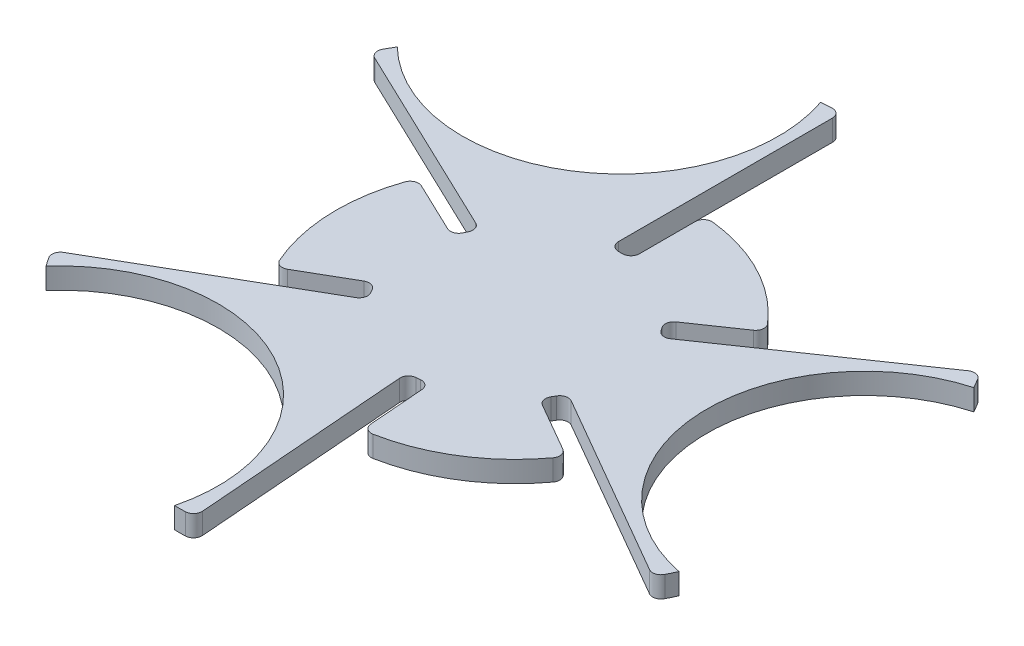
SolidWorks part; units mm, degrees
ref_plane "前基準面" through (0, 0, 0) normal (0, 0, 1) x (1, 0, 0)
ref_plane "上基準面" through (0, 0, 0) normal (0, 1, 0) x (1, 0, 0)
ref_plane "右基準面" through (0, 0, 0) normal (1, 0, 0) x (0, 0, -1)
sketch "草圖1" plane through (0, 0, 0) normal (0, 1, 0) x (1, 0, 0)
  line L2 (37.9923, -19.0481) -> (22.9006, -10.3349)
  line L8 (-2.5, 42.4264) -> (-2.5, 25)
  line L9 (-2.5, 25) -> (2.5, 25)
  line L10 (2.5, 42.4264) -> (2.5, 25)
  line L11 (22.9006, -10.3349) -> (20.4006, -14.6651)
  line L12 (35.4923, -23.3783) -> (20.4006, -14.6651)
  line L13 (-35.4923, -23.3783) -> (-20.4006, -14.6651)
  line L14 (-20.4006, -14.6651) -> (-22.9006, -10.3349)
  line L15 (-37.9923, -19.0481) -> (-22.9006, -10.3349)
  line L16 (20.6126, 14.1465) -> (0, 0) construction
  line L17 (4.4373, -24.7297) -> (5.793, -42.1033)
  line L18 (22.0272, 12.0852) -> (36.3953, 21.9461)
  line L19 (19.1979, 16.2077) -> (33.566, 26.0686)
  line L20 (19.1979, 16.2077) -> (22.0272, 12.0852)
  line L21 (-0.5475, -25.1187) -> (0.8082, -42.4923)
  line L22 (4.4373, -24.7297) -> (-0.5475, -25.1187)
  line L23 (-23.6352, 8.522) -> (-39.3591, 16.0347)
  line L24 (-21.4797, 13.0335) -> (-37.2035, 20.5462)
  line L25 (-23.6352, 8.522) -> (-21.4797, 13.0335)
  arc A35 (-2.5, 42.4264) -> (-37.2035, 20.5462) centre (0, 0) ccw
  circle A36 centre (0, 0) radius 25 construction
  arc A37 (37.9923, -19.0481) -> (36.3953, 21.9461) centre (0, 0) ccw
  arc A38 (-35.4923, -23.3783) -> (0.8082, -42.4923) centre (0, 0) ccw
  arc A39 (33.566, 26.0686) -> (2.5, 42.4264) centre (0, 0) ccw
  arc A40 (-39.3591, 16.0347) -> (-37.9923, -19.0481) centre (0, 0) ccw
  arc A41 (5.793, -42.1033) -> (35.4923, -23.3783) centre (0, 0) ccw
  point P1 (0, 25)
  dimension "D1" = 85
  dimension "D2" = 5
  dimension "D3" = 50
  dimension "D4" = 55.538
  dimension "D5" = 3
extrude "填料-伸長1" add sketch "草圖1" against normal blind 5
sketch "草圖2" plane through (0, 0, 0) normal (0, 1, 0) x (1, 0, 0)
  line L0 (-35.4923, -23.3783) -> (-67.9982, -42.1455)
  line L1 (0.8082, -42.4923) -> (3.7282, -79.9131)
  line L2 (-37.2727, -70.7866) -> (0, 0) construction
  line L3 (-0.5475, -25.1187) -> (0.8082, -42.4923) construction
  line L4 (-35.4923, -23.3783) -> (-20.4006, -14.6651) construction
  line L5 (-2.5, 42.4264) -> (-2.5, 79.9609)
  line L6 (-37.2035, 20.5462) -> (-71.0709, 36.7278)
  line L7 (37.9923, -19.0481) -> (70.4982, -37.8154)
  line L8 (36.3953, 21.9461) -> (67.3426, 43.1853)
  arc A0 (-65.4348, -46.0248) -> (-0.9208, -79.9947) centre (0, 0) ccw construction
  arc A1 (-0.9208, -79.9947) -> (-65.4348, -46.0248) centre (-37.2727, -70.7866) ccw
  arc A2 (-68.817, 40.7948) -> (-7.1413, 79.6806) centre (-42.6667, 67.6724) ccw
  arc A3 (-67.9982, -42.1455) -> (-65.4348, -46.0248) centre (0, 0) ccw
  arc A4 (-0.9208, -79.9947) -> (3.7282, -79.9131) centre (0, 0) ccw
  arc A5 (-35.4923, -23.3783) -> (0.8082, -42.4923) centre (0, 0) ccw construction
  arc A6 (-2.5, 79.9609) -> (-7.1413, 79.6806) centre (0, 0) ccw
  arc A7 (-68.817, 40.7948) -> (-71.0709, 36.7278) centre (0, 0) ccw
  arc A8 (69.7378, 39.1999) -> (72.5761, -33.6558) centre (79.9394, 3.1142) ccw
  arc A9 (70.4982, -37.8154) -> (72.5761, -33.6558) centre (0, 0) ccw
  arc A10 (69.7378, 39.1999) -> (67.3426, 43.1853) centre (0, 0) ccw
  arc A11 (-35.4923, -23.3783) -> (0.8082, -42.4923) centre (0, 0) ccw
  arc A12 (-2.5, 42.4264) -> (-37.2035, 20.5462) centre (0, 0) ccw
  arc A13 (37.9923, -19.0481) -> (36.3953, 21.9461) centre (0, 0) ccw
  dimension "D2" = 3
  dimension "D1" = 37.5
extrude "填料-伸長2" add sketch "草圖2" against normal up to surface (5 mm away) contours A11 L0 A3 A1 | A11 A1 A4 L1 | A13 L7 A9 A8 | A13 A8 A10 L8 | A12 L5 A6 A2 | A12 A2 A7 L6 up to face at (0, -5, 0)
fillet "圓角1" radius 2 24 edges at (-2.5, -2.5, -25) (2.5, -2.5, -25) (22.9006, -2.5, 10.3349) (20.4006, -2.5, 14.6651) (-20.4006, -2.5, 14.6651) (-22.9006, -2.5, 10.3349) (22.0272, -2.5, -12.0852) (19.1979, -2.5, -16.2077) (33.566, -2.5, -26.0686) (2.5, -2.5, -42.4264) (-21.4797, -2.5, -13.0335) (-23.6352, -2.5, -8.522) (-39.3591, -2.5, -16.0347) (-37.9923, -2.5, 19.0481) (4.4373, -2.5, 24.7297) (-0.5475, -2.5, 25.1187) (5.793, -2.5, 42.1033) (35.4923, -2.5, 23.3783) (70.4982, -2.5, 37.8154) (67.3426, -2.5, -43.1853) (-2.5, -2.5, -79.9609) (-71.0709, -2.5, -36.7278) (-67.9982, -2.5, 42.1455) (3.7282, -2.5, 79.9131)
